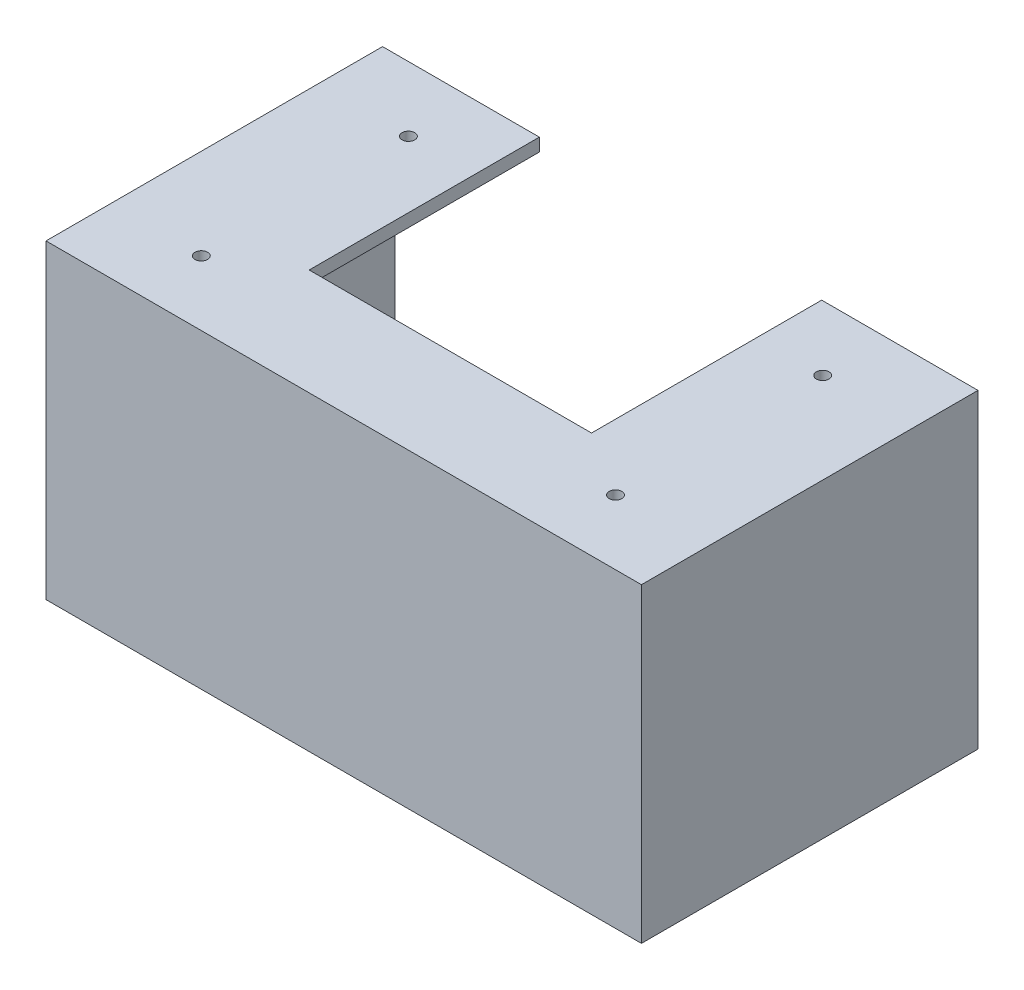
SolidWorks part; units mm, degrees
ref_plane "Front Plane" through (0, 0, 0) normal (0, 0, 1) x (1, 0, 0)
ref_plane "Top Plane" through (0, 0, 0) normal (0, 1, 0) x (1, 0, 0)
ref_plane "Right Plane" through (0, 0, 0) normal (1, 0, 0) x (0, 0, -1)
sketch "Sketch1" plane through (0, 0, 0) normal (0, 0, 1) x (1, 0, 0)
  line L1 (0, 0) -> (139.7, 0)
  line L2 (0, 0) -> (0, -69.85)
  line L3 (0, -69.85) -> (139.7, -69.85)
  line L4 (139.7, 0) -> (139.7, -69.85)
  line L5 (-3.0208, 3.175) -> (143.0292, 3.175)
  line L6 (-3.0208, 3.175) -> (-3.0208, -73.025)
  line L7 (-3.0208, -73.025) -> (143.0292, -73.025)
  line L8 (143.0292, 3.175) -> (143.0292, -73.025)
  dimension "D1" = 139.7
  dimension "D2" = 69.85
  dimension "D3" = 146.05
  dimension "D4" = 76.2
  dimension "D5" = 3.175
extrude "Boss-Extrude1" add sketch "Sketch1" along normal blind 76.2
sketch "Sketch2" plane through (0, 0, 76.2) normal (0, 0, 1) x (1, 0, 0)
  line L1 (-3.0208, 3.175) -> (143.0292, 3.175)
  line L2 (-3.0208, 3.175) -> (-3.0208, -73.025)
  line L3 (-3.0208, -73.025) -> (143.0292, -73.025)
  line L4 (143.0292, 3.175) -> (143.0292, -73.025)
extrude "Boss-Extrude2" add sketch "Sketch2" along normal blind 6.35
sketch "Sketch3" plane through (0, 3.175, 0) normal (0, 1, 0) x (1, 0, 0)
  line L0 (70.0042, 0) -> (70.0042, -82.55) construction
  line L1 (143.0292, 0) -> (-3.0208, 0) construction
  line L2 (143.0292, -82.55) -> (-3.0208, -82.55) construction
  line L3 (-3.0208, -41.275) -> (143.0292, -41.275) construction
  line L4 (-3.0208, -82.55) -> (-3.0208, 0) construction
  line L5 (143.0292, -82.55) -> (143.0292, 0) construction
  circle A0 centre (19.2042, -15.875) radius 1.55
  circle A1 centre (120.8042, -15.875) radius 1.55
  circle A2 centre (120.8042, -66.675) radius 1.55
  circle A3 centre (19.2042, -66.675) radius 1.55
  dimension "D3" = 3.1
  dimension "D6" = 3.1
  dimension "D9" = 3.1
  dimension "D12" = 3.1
  dimension "D1" = 25.4
  dimension "D2" = 50.8
  dimension "D4" = 50.8
  dimension "D5" = 25.4
  dimension "D7" = 50.8
  dimension "D8" = 25.4
  dimension "D10" = 25.4
  dimension "D11" = 50.8
extrude "Cut-Extrude1" cut sketch "Sketch3" against normal blind 6.35
sketch "Sketch4" plane through (0, 3.175, 0) normal (0, 1, 0) x (1, 0, 0)
  line L0 (143.0292, 0) -> (-3.0208, 0) construction
  line L1 (35.437, 0) -> (104.6884, 0)
  line L2 (35.437, 0) -> (35.437, -56.4527)
  line L3 (35.437, -56.4527) -> (104.6884, -56.4527)
  line L4 (104.6884, 0) -> (104.6884, -56.4527)
extrude "Cut-Extrude2" cut sketch "Sketch4" against normal blind 25.4
